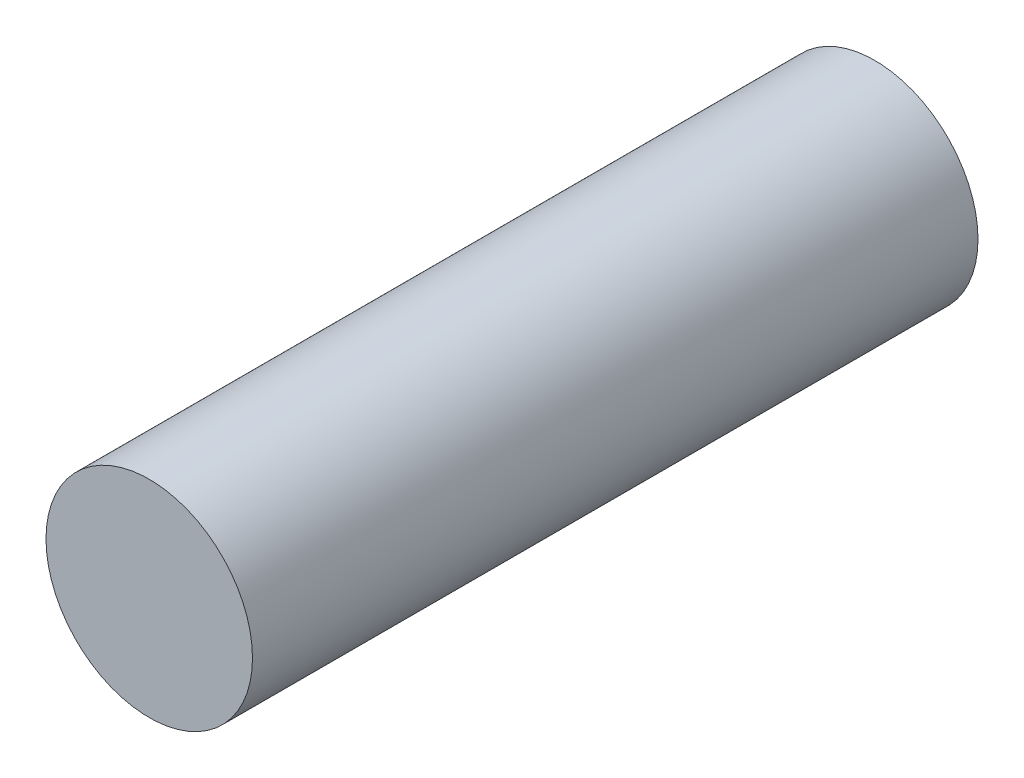
SolidWorks part; units mm, degrees
ref_plane "Front Plane" through (0, 0, 0) normal (0, 0, 1) x (1, 0, 0)
ref_plane "Top Plane" through (0, 0, 0) normal (0, 1, 0) x (1, 0, 0)
ref_plane "Right Plane" through (0, 0, 0) normal (1, 0, 0) x (0, 0, -1)
sketch "草圖1" plane through (0, 0, 0) normal (0, 0, 1) x (1, 0, 0)
  circle A0 centre (0, 0) radius 9.25
extrude "填料-伸長1" add sketch "草圖1" along normal blind 65
